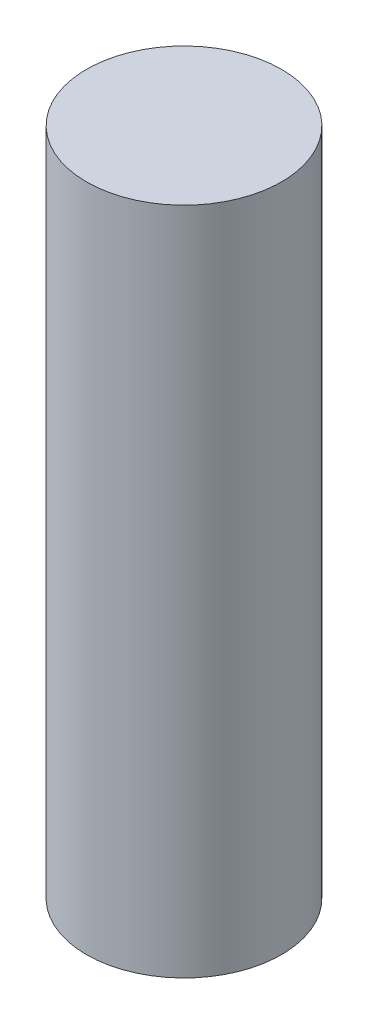
SolidWorks part; units mm, degrees
ref_plane "Plano frontal" through (0, 0, 0) normal (0, 0, 1) x (1, 0, 0)
ref_plane "Plano superior" through (0, 0, 0) normal (0, 1, 0) x (1, 0, 0)
ref_plane "Plano direito" through (0, 0, 0) normal (1, 0, 0) x (0, 0, -1)
sketch "Esboço1" plane through (0, 0, 0) normal (0, 1, 0) x (1, 0, 0)
  circle A0 centre (0, 0) radius 9.5
  dimension "D1" = 19
extrude "Ressalto-extrusão1" add sketch "Esboço1" along normal blind 65.2
